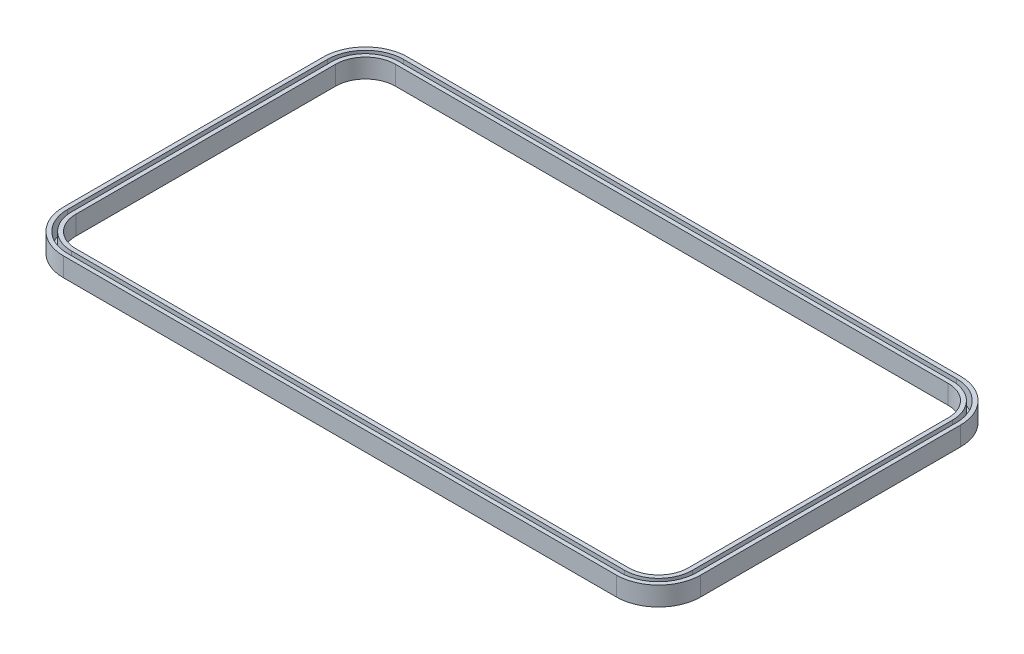
SolidWorks part; units mm, degrees
ref_plane "前视基准面" through (0, 0, 0) normal (0, 0, 1) x (1, 0, 0)
ref_plane "上视基准面" through (0, 0, 0) normal (0, 1, 0) x (1, 0, 0)
ref_plane "右视基准面" through (0, 0, 0) normal (1, 0, 0) x (0, 0, -1)
other "Configuration Table"
sketch "草图2" plane through (0, 0, 0) normal (0, 1, 0) x (1, 0, 0)
  line L1 (-167, 104) -> (167, 104)
  line L2 (-192.5, 78.5) -> (-192.5, -78.5)
  line L3 (-167, -104) -> (167, -104)
  line L4 (192.5, 78.5) -> (192.5, -78.5)
  line L5 (-192.5, 104) -> (192.5, -104) construction
  line L6 (-192.5, -104) -> (192.5, 104) construction
  arc A0 (167, 104) -> (192.5, 78.5) centre (167, 78.5) cw
  arc A1 (167, -104) -> (192.5, -78.5) centre (167, -78.5) ccw
  arc A2 (-192.5, -78.5) -> (-167, -104) centre (-167, -78.5) ccw
  arc A3 (-167, 104) -> (-192.5, 78.5) centre (-167, 78.5) ccw
  point P0 (0, 0)
  dimension "D3" = 25.5
  dimension "D1" = 385
  dimension "D2" = 208
extrude "凸台-拉伸1" add sketch "草图2" along normal blind 11.5
sketch "草图3" plane through (0, 11.5, 0) normal (0, 1, 0) x (1, 0, 0)
  line L0 (-167, -104) -> (167, -104) construction
  line L1 (-167, 96.5) -> (167, 96.5)
  line L2 (-185, 78.5) -> (-185, -78.5)
  line L3 (-167, -96.5) -> (167, -96.5)
  line L4 (185, 78.5) -> (185, -78.5)
  line L5 (-185, 96.5) -> (185, -96.5) construction
  line L6 (-185, -96.5) -> (185, 96.5) construction
  line L7 (-192.5, 78.5) -> (-192.5, -78.5) construction
  arc A0 (167, 96.5) -> (185, 78.5) centre (167, 78.5) cw
  arc A1 (167, -96.5) -> (185, -78.5) centre (167, -78.5) ccw
  arc A2 (-185, -78.5) -> (-167, -96.5) centre (-167, -78.5) ccw
  arc A3 (-167, 96.5) -> (-185, 78.5) centre (-167, 78.5) ccw
  point P0 (0, 0)
  dimension "D4" = 18
  dimension "D1" = 370
  dimension "D2" = 7.5
  dimension "D3" = 7.5
extrude "切除-拉伸1" cut sketch "草图3" against normal through all and the other way through all
sketch "草图6" plane through (0, 11.5, 0) normal (0, 1, 0) x (1, 0, 0)
  line L0 (-192.5, 78.5) -> (-192.5, -78.5) construction
  line L1 (-167, 101.5) -> (167, 101.5)
  line L2 (-190, 78.5) -> (-190, -78.5)
  line L3 (-167, -101.5) -> (167, -101.5)
  line L4 (190, 78.5) -> (190, -78.5)
  line L5 (-190, 101.5) -> (190, -101.5) construction
  line L6 (-190, -101.5) -> (190, 101.5) construction
  line L7 (167, 104) -> (-167, 104) construction
  line L8 (-185, 78.5) -> (-185, -78.5) construction
  line L9 (-167, 99) -> (167, 99)
  line L10 (-187.5, 78.5) -> (-187.5, -78.5)
  line L11 (-167, -99) -> (167, -99)
  line L12 (187.5, 78.5) -> (187.5, -78.5)
  line L13 (-187.5, 99) -> (187.5, -99) construction
  line L14 (-187.5, -99) -> (187.5, 99) construction
  line L15 (167, 96.5) -> (-167, 96.5) construction
  arc A0 (167, -101.5) -> (190, -78.5) centre (167, -78.5) ccw
  arc A1 (167, 101.5) -> (190, 78.5) centre (167, 78.5) cw
  arc A2 (-167, 101.5) -> (-190, 78.5) centre (-167, 78.5) ccw
  arc A3 (-190, -78.5) -> (-167, -101.5) centre (-167, -78.5) ccw
  arc A4 (-167, 99) -> (-187.5, 78.5) centre (-167, 78.5) ccw
  arc A5 (167, 99) -> (187.5, 78.5) centre (167, 78.5) cw
  arc A6 (167, -99) -> (187.5, -78.5) centre (167, -78.5) ccw
  arc A7 (-187.5, -78.5) -> (-167, -99) centre (-167, -78.5) ccw
  point P0 (0, 0)
  point P22 (0, 0)
  dimension "D3" = 23
  dimension "D6" = 20.5
  dimension "D1" = 2.5
  dimension "D2" = 2.5
  dimension "D4" = 2.5
  dimension "D5" = 2.5
extrude "切除-拉伸3" cut sketch "草图6" against normal blind 10
